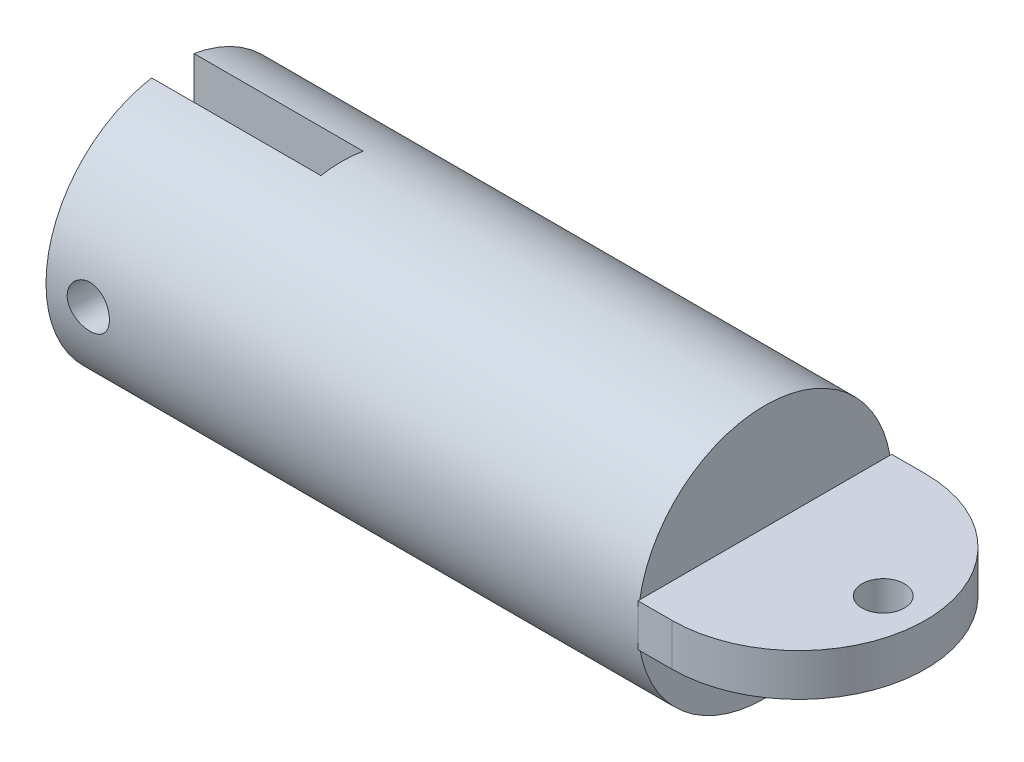
SolidWorks part; units mm, degrees
ref_plane "Front Plane" through (0, 0, 0) normal (0, 0, 1) x (1, 0, 0)
ref_plane "Top Plane" through (0, 0, 0) normal (0, 1, 0) x (1, 0, 0)
ref_plane "Right Plane" through (0, 0, 0) normal (1, 0, 0) x (0, 0, -1)
sketch "Sketch2" plane through (0, 0, 0) normal (1, 0, 0) x (0, 0, -1)
  circle A0 centre (0, 0) radius 15
  dimension "D1" = 30
extrude "Boss-Extrude1" add sketch "Sketch2" against normal blind 70
sketch "Sketch3" plane through (0, 0, 0) normal (0, 1, 0) x (1, 0, 0)
  line L0 (-70, 15) -> (-70, -15) construction
  line L1 (-70, 2.5) -> (-50, 2.5)
  line L2 (-70, 2.5) -> (-70, -2.5)
  line L3 (-70, -2.5) -> (-50, -2.5)
  line L4 (-50, 2.5) -> (-50, -2.5)
  line L5 (0, 15) -> (-70, 15) construction
  dimension "D1" = 5
  dimension "D2" = 20
  dimension "D3" = 0
  dimension "D4" = 12.5
extrude "Cut-Extrude1" cut sketch "Sketch3" against normal through all and the other way through all
sketch "Sketch6" plane through (0, 0, 0) normal (0, 0, 1) x (1, 0, 0)
  line L0 (-70, 14.7902) -> (-70, -14.7902) construction
  circle A0 centre (-65, 0) radius 2.5
  dimension "D2" = 5
  dimension "D1" = 5
  dimension "D3" = 0
extrude "Cut-Extrude2" cut sketch "Sketch6" against normal through all and the other way through all
sketch "Sketch7" plane through (0, 0, 0) normal (1, 0, 0) x (0, 1, 0)
  line L0 (-2.5, 15) -> (-2.5, -15)
  line L1 (-2.5, 15) -> (2.5, 15)
  line L2 (-2.5, -15) -> (2.5, -15)
  line L3 (2.5, 15) -> (2.5, -15)
  line L4 (-2.5, 15) -> (2.5, -15) construction
  line L5 (-2.5, -15) -> (2.5, 15) construction
  point P1 (0, 0)
  dimension "D1" = 5
extrude "Boss-Extrude2" add sketch "Sketch7" along normal blind 4
sketch "Sketch8" plane through (0, -2.5, 0) normal (0, -1, 0) x (1, 0, 0)
  line L0 (4, 15) -> (4, -15) construction
  line L1 (4, 15) -> (4, -15)
  arc A0 (4, -15) -> (4, 15) centre (4, 0) ccw
extrude "Boss-Extrude3" add sketch "Sketch8" against normal blind 5
sketch "Sketch9" plane through (0, -2.5, 0) normal (0, -1, 0) x (1, 0, 0)
  circle A0 centre (14, 0) radius 2.5
  arc A1 (4, -15) -> (4, 15) centre (4, 0) ccw construction
  point P5 (19, 0)
  dimension "D1" = 5
  dimension "D2" = 5
extrude "Cut-Extrude3" cut sketch "Sketch9" against normal through all and the other way through all
